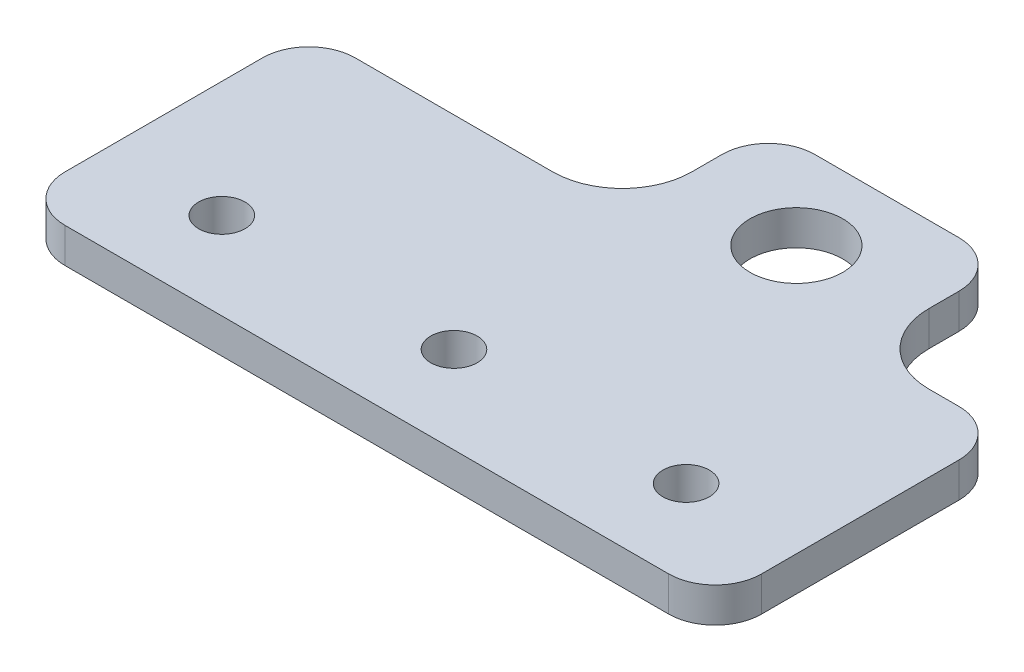
SolidWorks part; units mm, degrees
material "C-玻璃纤维"
ref_plane "前视基准面" through (0, 0, 0) normal (0, 0, 1) x (1, 0, 0)
ref_plane "上视基准面" through (0, 0, 0) normal (0, 1, 0) x (1, 0, 0)
ref_plane "右视基准面" through (0, 0, 0) normal (1, 0, 0) x (0, 0, -1)
other "Configuration Table"
sketch "草图1" plane through (0, 0, 0) normal (0, 1, 0) x (1, 0, 0)
  line L0 (-30, -5) -> (30, -5) construction
  line L1 (-30, 12.5) -> (30, 12.5)
  line L2 (-30, 12.5) -> (-30, -12.5)
  line L3 (-30, -12.5) -> (30, -12.5)
  line L4 (30, 12.5) -> (30, -12.5)
  line L5 (-30, 12.5) -> (30, -12.5) construction
  line L6 (-30, -12.5) -> (30, 12.5) construction
  line L7 (-30, 12.5) -> (10.9191, 31.5809)
  line L8 (10.9191, 31.5809) -> (30, 12.5)
  line L9 (-30, 12.5) -> (-30, 31.5809)
  line L10 (-30, 31.5809) -> (30, 31.5809)
  line L11 (30, 31.5809) -> (30, 12.5)
  circle A1 centre (0, -5) radius 2
  circle A2 centre (-20, -5) radius 2
  circle A3 centre (20, -5) radius 2
  point P0 (0, 0)
  dimension "D3" = 7.5
  dimension "D4" = 4
  dimension "D5" = 20
  dimension "D6" = 20
  dimension "D1" = 25
  dimension "D2" = 60
  dimension "D7" = 45
  dimension "D8" = 25
extrude "凸台-拉伸1" add sketch "草图1" along normal blind 3 contours L4 L1 L2 L3 A3 A2 A1 | L8 L7 L1
sketch "草图2" plane through (0, 3, 0) normal (0, 1, 0) x (1, 0, 0)
  line L0 (-30, -12.5) -> (30, -12.5) construction
  circle A0 centre (7, 17.5) radius 4
  dimension "D1" = 8
  dimension "D2" = 30
  dimension "D3" = 7
extrude "切除-拉伸1" cut sketch "草图2" against normal blind 3
sketch "草图3" plane through (0, 3, 0) normal (0, 1, 0) x (1, 0, 0)
  line L0 (-30, 12.5) -> (10.9191, 31.5809) construction
  line L1 (-30, 12.5) -> (-3, 12.5)
  line L2 (-30, 12.5) -> (-30, 25.0903)
  line L3 (-30, 25.0903) -> (-3, 25.0903)
  line L4 (-3, 12.5) -> (-3, 25.0903)
  line L5 (10.9191, 31.5809) -> (30, 12.5) construction
  line L6 (-3, 25.0903) -> (17.4097, 25.0903)
  line L7 (-3, 25.0903) -> (-3, 35.0903)
  line L8 (-3, 35.0903) -> (17.4097, 35.0903)
  line L9 (17.4097, 25.0903) -> (17.4097, 35.0903)
  line L10 (30, 12.5) -> (17.4097, 12.5)
  line L11 (30, 12.5) -> (30, 25.0903)
  line L12 (30, 25.0903) -> (17.4097, 25.0903)
  line L13 (17.4097, 12.5) -> (17.4097, 25.0903)
  point P17 (0, 0)
  line M18 (30, 12.5) -> (10.9191, 31.5809)
  line M19 (10.9191, 31.5809) -> (-30, 12.5)
  dimension "D1" = 27
  dimension "D2" = 10
extrude "切除-拉伸2" cut sketch "草图3" against normal blind 10 contours L1 L4 M19 | L6 M19 M18 | L13 L10 M18
fillet "圆角1" radius 6 2 edges at (17.4097, 1.5, -12.5) (-3, 1.5, -12.5)
fillet "圆角2" radius 4 2 edges at (17.4097, 1.5, -25.0903) (-3, 1.5, -25.0903)
fillet "圆角3" radius 4 4 edges at (30, 1.5, -12.5) (30, 1.5, 12.5) (-30, 1.5, 12.5) (-30, 1.5, -12.5)
